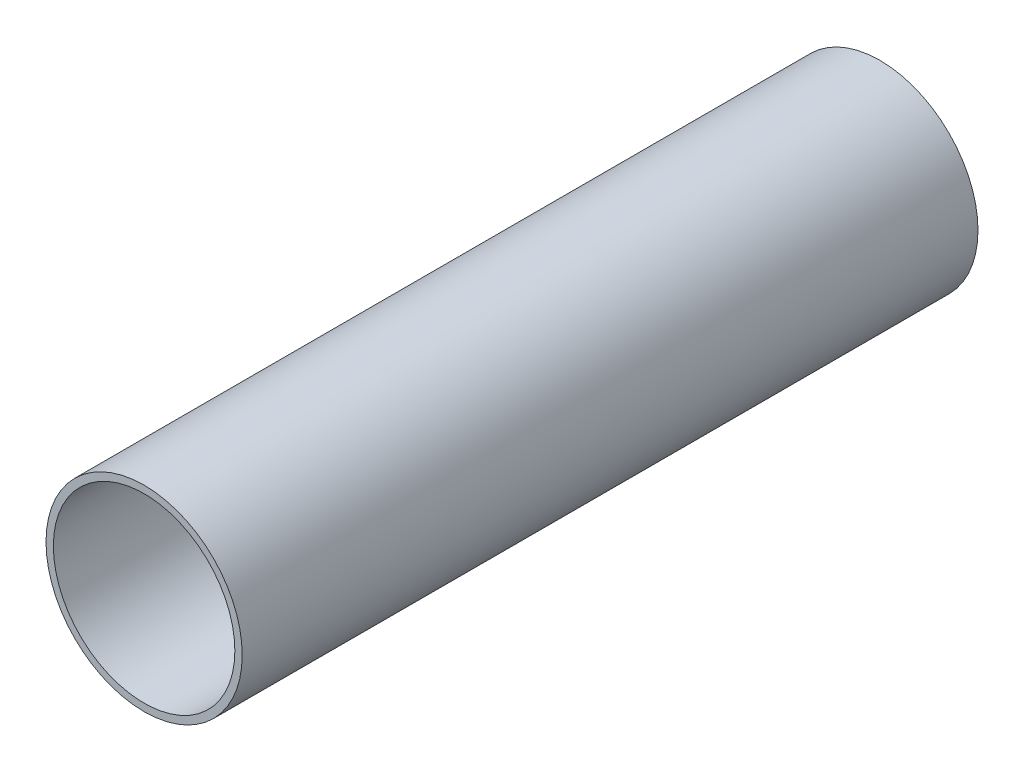
SolidWorks part; units mm, degrees
ref_plane "Front Plane" through (0, 0, 0) normal (0, 0, 1) x (1, 0, 0)
ref_plane "Top Plane" through (0, 0, 0) normal (0, 1, 0) x (1, 0, 0)
ref_plane "Right Plane" through (0, 0, 0) normal (1, 0, 0) x (0, 0, -1)
sketch "Sketch1" plane through (0, 0, 0) normal (0, 0, 1) x (1, 0, 0)
  circle A0 centre (0, 0) radius 20
  circle A1 centre (0, 0) radius 18.5
  dimension "D1" = 40
  dimension "D2" = 37
extrude "Boss-Extrude1" add sketch "Sketch1" along normal blind 150
